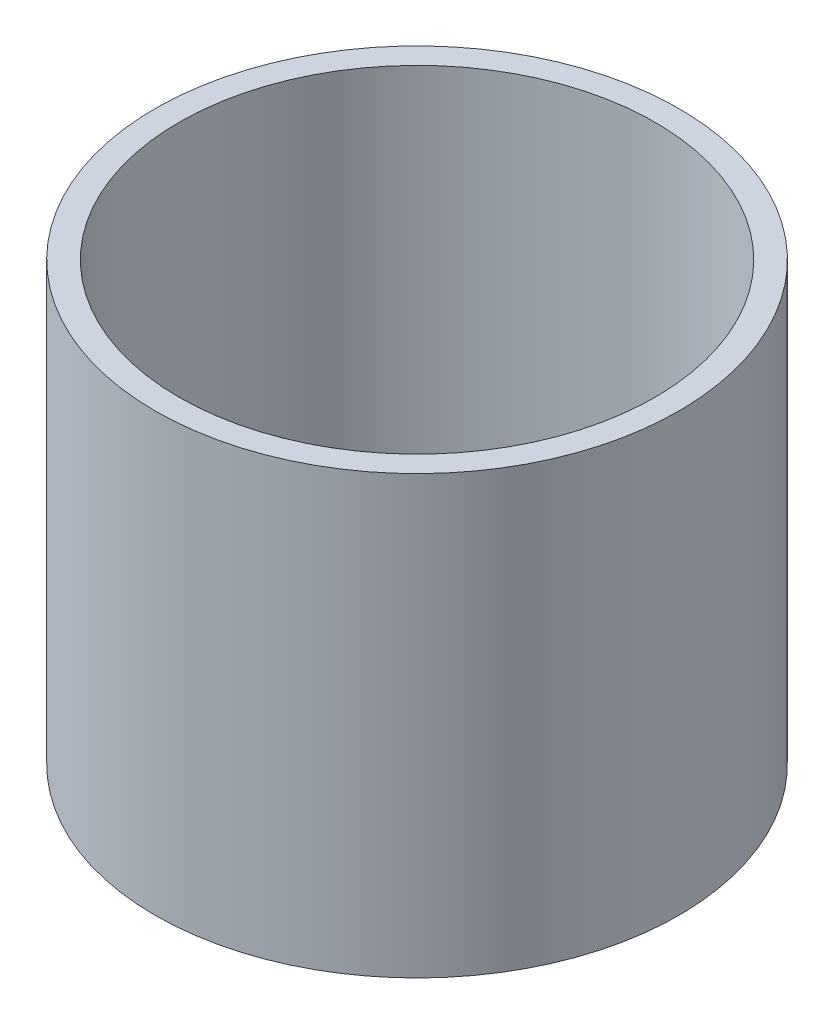
SolidWorks part; units mm, degrees
ref_plane "Front Plane" through (0, 0, 0) normal (0, 0, 1) x (1, 0, 0)
ref_plane "Top Plane" through (0, 0, 0) normal (0, 1, 0) x (1, 0, 0)
ref_plane "Right Plane" through (0, 0, 0) normal (1, 0, 0) x (0, 0, -1)
sketch "Sketch1" plane through (0, 0, 0) normal (0, 1, 0) x (1, 0, 0)
  circle A0 centre (0, 0) radius 25.4
  circle A1 centre (0, 0) radius 27.94
  dimension "D1" = 50.8
  dimension "D2" = 55.88
extrude "Boss-Extrude1" add sketch "Sketch1" along normal blind 46.6
